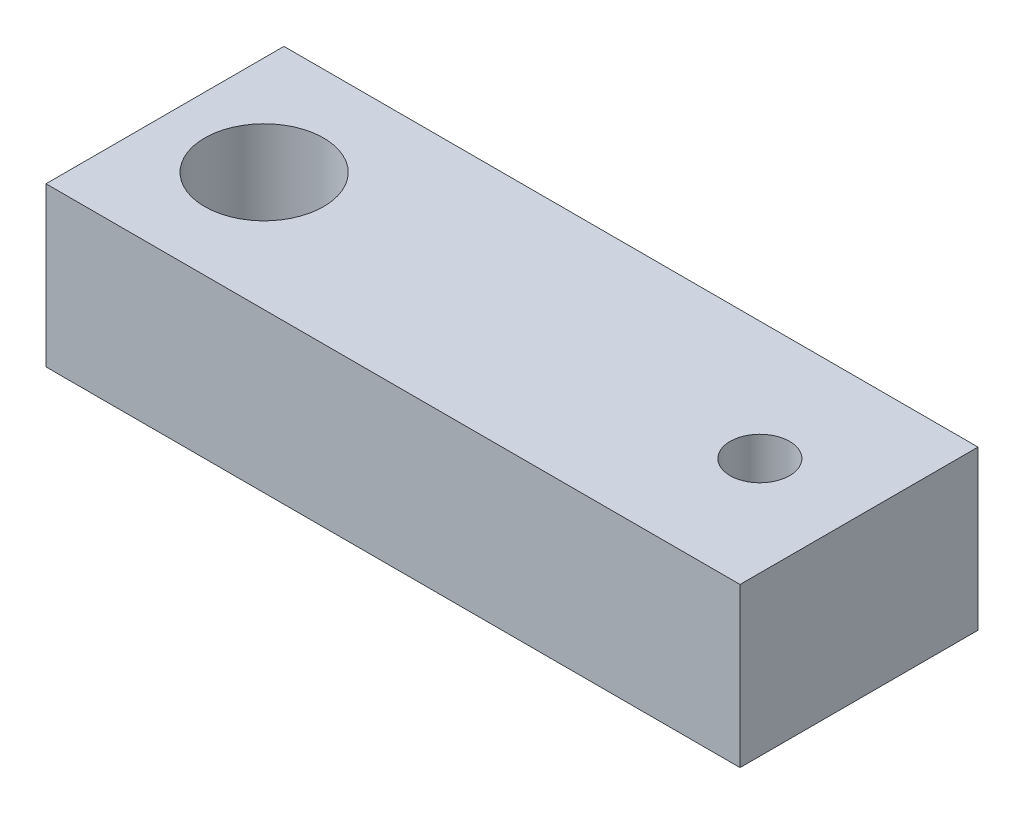
SolidWorks part; units mm, degrees
ref_plane "Front Plane" through (0, 0, 0) normal (0, 0, 1) x (1, 0, 0)
ref_plane "Top Plane" through (0, 0, 0) normal (0, 1, 0) x (1, 0, 0)
ref_plane "Right Plane" through (0, 0, 0) normal (1, 0, 0) x (0, 0, -1)
sketch "Sketch2" plane through (0, 0, 0) normal (0, 1, 0) x (1, 0, 0)
  line L0 (0, 6) -> (35, 6) construction
  line L1 (0, 0) -> (35, 0)
  line L2 (0, 0) -> (0, 12)
  line L3 (0, 12) -> (35, 12)
  line L4 (35, 0) -> (35, 12)
  circle A0 centre (5, 6) radius 3
  circle A1 centre (30, 6) radius 1.5
  dimension "D3" = 3
  dimension "D4" = 6
  dimension "D5" = 25
  dimension "D6" = 5
  dimension "D1" = 12
  dimension "D2" = 35
extrude "Boss-Extrude1" add sketch "Sketch2" along normal blind 8
